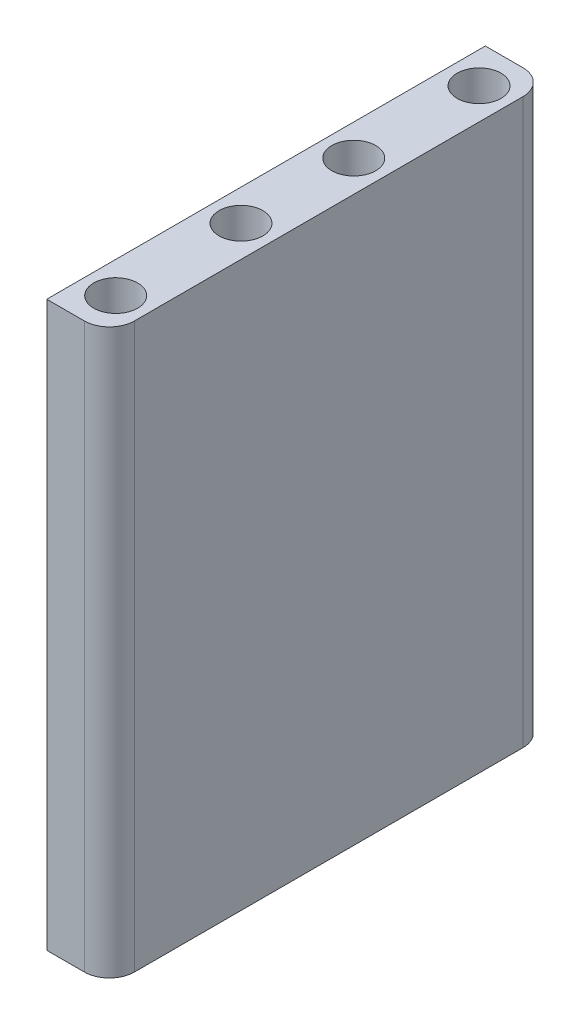
SolidWorks part; units mm, degrees
ref_plane "Front Plane" through (0, 0, 0) normal (0, 0, 1) x (1, 0, 0)
ref_plane "Top Plane" through (0, 0, 0) normal (0, 1, 0) x (1, 0, 0)
ref_plane "Right Plane" through (0, 0, 0) normal (1, 0, 0) x (0, 0, -1)
sketch "Sketch1" plane through (0, 0, 0) normal (0, 1, 0) x (1, 0, 0)
  line L1 (0, 35) -> (3, 35)
  line L2 (0, 35) -> (0, 0)
  line L3 (0, 0) -> (3, 0)
  line L4 (5, 33) -> (5, 2)
  circle A0 centre (2.5, 32) radius 1.75
  circle A1 centre (2.5, 22) radius 1.75
  circle A2 centre (2.5, 13) radius 1.75
  circle A3 centre (2.5, 3) radius 1.75
  arc A4 (3, 0) -> (5, 2) centre (3, 2) ccw
  arc A5 (3, 35) -> (5, 33) centre (3, 33) cw
  point P12 (0.3652, 23.0899)
  point P13 (0.3652, 16.9663)
  point P14 (0.3652, 1.7978)
  point P15 (0, 0)
  point P16 (0, 0)
  point P17 (0, 0)
  point P18 (-0.7605, 19.014)
  point P19 (7.2749, 8.1039)
  point P21 (0, 0)
  point P24 (5, 0)
  point P27 (5, 35)
  dimension "D3" = 3.5
  dimension "D9" = 2
  dimension "D1" = 5
  dimension "D2" = 35
  dimension "D4" = 2.5
  dimension "D5" = 3
  dimension "D6" = 10
  dimension "D7" = 9
  dimension "D8" = 10
extrude "Boss-Extrude1" add sketch "Sketch1" along normal blind 45
